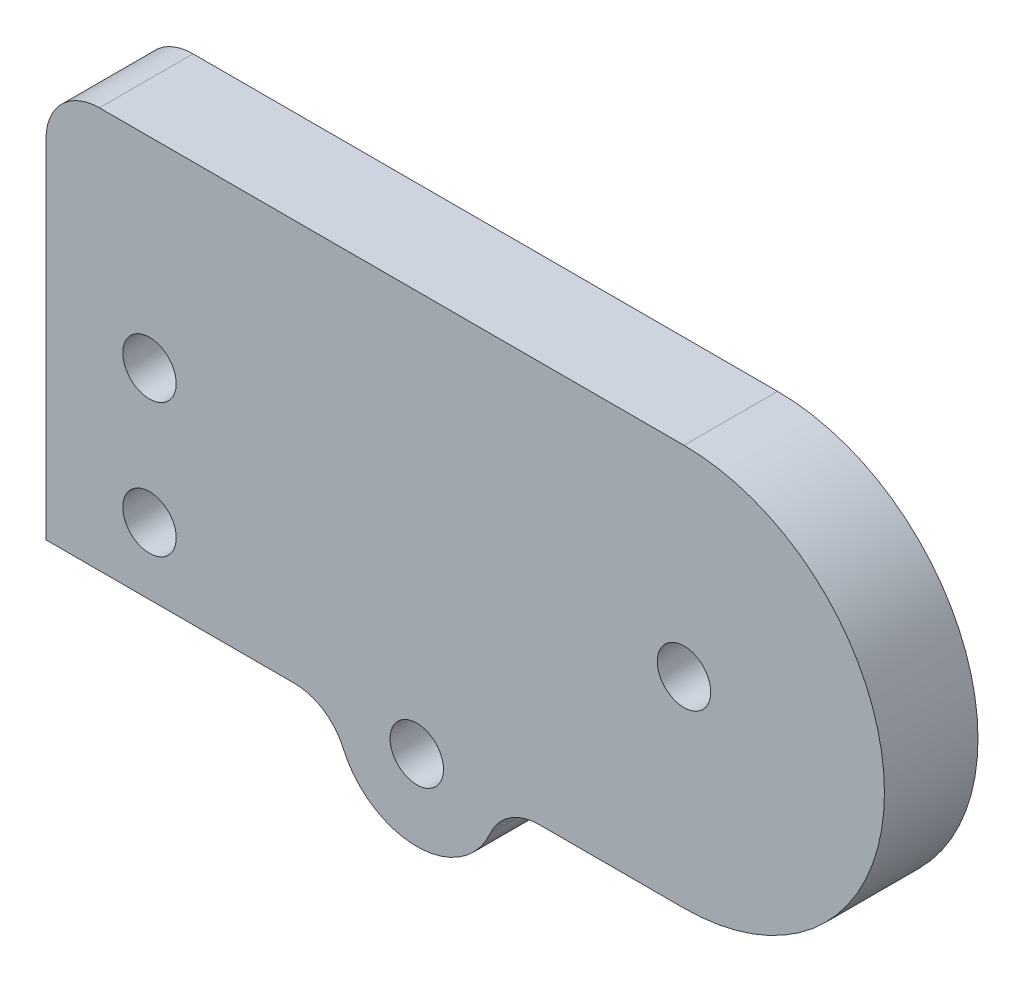
SolidWorks part; units mm, degrees
ref_plane "Front Plane" through (0, 0, 0) normal (0, 0, 1) x (1, 0, 0)
ref_plane "Top Plane" through (0, 0, 0) normal (0, 1, 0) x (1, 0, 0)
ref_plane "Right Plane" through (0, 0, 0) normal (1, 0, 0) x (0, 0, -1)
sketch "Sketch1" plane through (0, 0, 0) normal (0, 0, 1) x (1, 0, 0)
  line L0 (0, 0) -> (0, 13)
  line L1 (2, 15) -> (23.873, 15)
  line L2 (23.873, 0) -> (18.4556, 0)
  line L3 (9.2904, 0) -> (0, 0)
  arc A0 (23.873, 15) -> (23.873, 0) centre (23.873, 7.5) cw
  arc A1 (16.6225, -1.2) -> (11.1234, -1.2) centre (13.873, 0) cw
  circle A2 centre (3.873, 7.5) radius 1
  circle A3 centre (23.873, 7.5) radius 1
  circle A4 centre (13.873, 0) radius 1
  circle A5 centre (3.873, 2.5) radius 1
  arc A6 (0, 13) -> (2, 15) centre (2, 13) cw
  arc A7 (18.4556, 0) -> (16.6225, -1.2) centre (18.4556, -2) ccw
  arc A8 (11.1234, -1.2) -> (9.2904, 0) centre (9.2904, -2) ccw
  point P16 (0, 6.5)
  point P20 (0, 15)
  dimension "D2" = 2
  dimension "D3" = 4
  dimension "D6" = 2
  dimension "D8" = 3
  dimension "D9" = 2
  dimension "D1" = 15
  dimension "D4" = 20
  dimension "D5" = 7.5
  dimension "D7" = 10
  dimension "D10" = 2.5
extrude "Boss-Extrude1" add sketch "Sketch1" along normal blind 3.5
